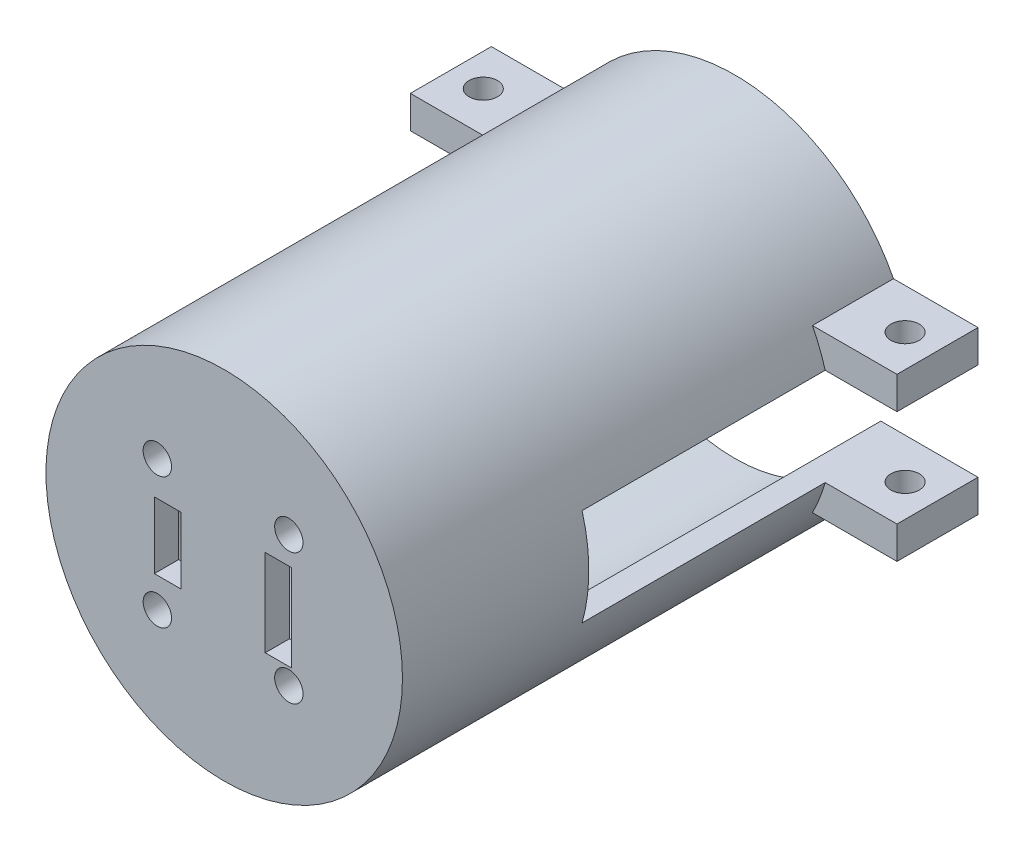
SolidWorks part; units mm, degrees
ref_plane "Front Plane" through (0, 0, 0) normal (0, 0, 1) x (1, 0, 0)
ref_plane "Top Plane" through (0, 0, 0) normal (0, 1, 0) x (1, 0, 0)
ref_plane "Right Plane" through (0, 0, 0) normal (1, 0, 0) x (0, 0, -1)
sketch "Sketch1" plane through (0, 0, 0) normal (0, 0, 1) x (1, 0, 0)
  circle A0 centre (0, 0) radius 19
  circle A1 centre (0, 0) radius 22
  dimension "D1" = 38
  dimension "D2" = 44
extrude "Boss-Extrude1" add sketch "Sketch1" along normal blind 60
sketch "Sketch2" plane through (0, 0, 60) normal (0, 0, 1) x (1, 0, 0)
  circle A1 centre (0, 0) radius 22
  circle A2 centre (0, 0) radius 22
  dimension "D1" = 0
extrude "Boss-Extrude2" add sketch "Sketch2" along normal blind 3
sketch "Sketch3" plane through (0, 0, 0) normal (0, 0, -1) x (-1, 0, 0)
  line L0 (-21.166, 6) -> (-18.0278, 6)
  line L1 (-21.166, -6) -> (-18.0278, -6)
  line L2 (18.0278, 6) -> (21.166, 6)
  line L3 (18.0278, -6) -> (21.166, -6)
  circle A0 centre (0, 0) radius 22 construction
  circle A1 centre (0, 0) radius 19 construction
  arc A2 (-21.166, 6) -> (-21.166, -6) centre (0, 0) ccw
  arc A3 (-18.0278, 6) -> (-18.0278, -6) centre (0, 0) ccw
  arc A4 (18.0278, -6) -> (18.0278, 6) centre (0, 0) ccw
  arc A5 (21.166, -6) -> (21.166, 6) centre (0, 0) ccw
  dimension "D1" = 6
  dimension "D2" = 6
  dimension "D3" = 6
  dimension "D4" = 6
extrude "Cut-Extrude1" cut sketch "Sketch3" against normal blind 40
sketch "Sketch8" plane through (0, 0, 60) normal (0, 0, -1) x (-1, 0, 0)
  line L1 (5.3034, 4.0791) -> (8.6211, 4.0791)
  line L2 (5.3034, 4.0791) -> (5.3034, -4.1253)
  line L3 (5.3034, -4.1253) -> (8.6211, -4.1253)
  line L4 (8.6211, 4.0791) -> (8.6211, -4.1253)
  line L5 (-5.0615, 4.9792) -> (-8.3021, 4.9792)
  line L6 (-5.0615, 4.9792) -> (-5.0615, -5.7456)
  line L7 (-5.0615, -5.7456) -> (-8.3021, -5.7456)
  line L8 (-8.3021, 4.9792) -> (-8.3021, -5.7456)
  circle A0 centre (-7.9763, -7.8163) radius 1.75
  circle A1 centre (-7.9763, 8.3437) radius 1.75
  circle A2 centre (8.2537, 8.3437) radius 1.75
  circle A3 centre (8.2537, -7.8163) radius 1.75
extrude "Cut-Extrude4" cut sketch "Sketch8" against normal through all
sketch "Sketch9" plane through (0, 0, 0) normal (0, 0, -1) x (-1, 0, 0)
  line L0 (0, 0) -> (-13.0072, 0) construction
  line L1 (-18.0278, 6) -> (-30.0278, 6)
  line L2 (-18.0278, 6) -> (-18.0278, 10)
  line L3 (-18.0278, 10) -> (-30.0278, 10)
  line L4 (-30.0278, 6) -> (-30.0278, 10)
  line L5 (0, 0) -> (0, 9) construction
  line L6 (-18.0278, -10) -> (-30.0278, -10)
  line L7 (-30.0278, -6) -> (-30.0278, -10)
  line L8 (-18.0278, -6) -> (-30.0278, -6)
  line L9 (-18.0278, -6) -> (-18.0278, -10)
  line L10 (18.0278, -6) -> (18.0278, -10)
  line L11 (18.0278, -6) -> (30.0278, -6)
  line L12 (30.0278, -6) -> (30.0278, -10)
  line L13 (18.0278, -10) -> (30.0278, -10)
  line L14 (18.0278, 10) -> (30.0278, 10)
  line L15 (30.0278, 6) -> (30.0278, 10)
  line L16 (18.0278, 6) -> (30.0278, 6)
  line L17 (18.0278, 6) -> (18.0278, 10)
  dimension "D1" = 4
  dimension "D2" = 12
extrude "Boss-Extrude3" add sketch "Sketch9" against normal blind 10
sketch "Sketch10" plane through (0, 10, 0) normal (0, 1, 0) x (1, 0, 0)
  line L0 (19.5959, 0) -> (30.0278, 0) construction
  line L1 (30.0278, -10) -> (30.0278, 0) construction
  line L2 (-30.0278, 0) -> (-19.5959, 0) construction
  line L3 (-30.0278, -10) -> (-30.0278, 0) construction
  circle A0 centre (-26.0278, -5) radius 1.75
  circle A1 centre (26.0278, -5) radius 1.75
  dimension "D1" = 5
  dimension "D2" = 3.5
  dimension "D3" = 4
  dimension "D4" = 5
  dimension "D5" = 3.5
  dimension "D6" = 4
extrude "Cut-Extrude5" cut sketch "Sketch10" against normal through all
